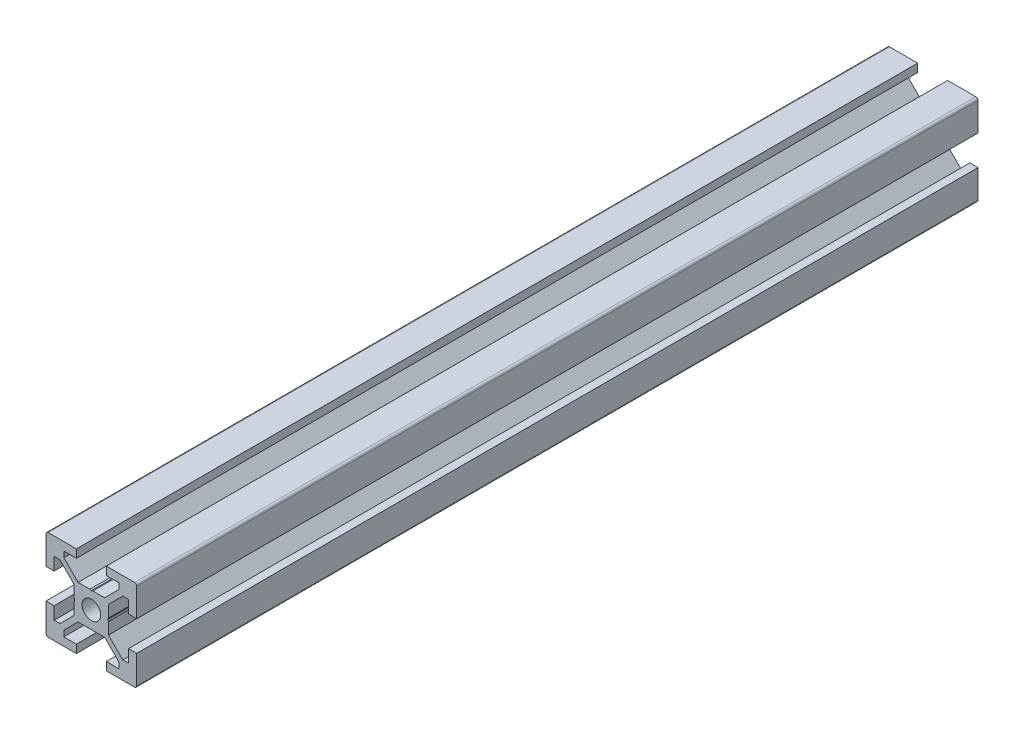
SolidWorks part; units mm, degrees
ref_plane "Front Plane" through (0, 0, 0) normal (0, 0, 1) x (1, 0, 0)
ref_plane "Top Plane" through (0, 0, 0) normal (0, 1, 0) x (1, 0, 0)
ref_plane "Right Plane" through (0, 0, 0) normal (1, 0, 0) x (0, 0, -1)
sketch "Sketch1" plane through (0, 0, 0) normal (0, 0, 1) x (1, 0, 0)
  line L0 (-3.3, 10) -> (-3.3, 8.2)
  line L1 (0, 0) -> (50000, 0) construction
  line L2 (-10, 3.3) -> (-10, 10)
  line L3 (-10, 10) -> (-3.3, 10)
  line L4 (0, 0) -> (0, 50000) construction
  line L5 (-10, -10) -> (10, 10) construction
  line L6 (-10, 10) -> (10, -10) construction
  line L7 (-2.9315, -3.78) -> (-0.34, -3.78)
  line L8 (-3.78, -2.9315) -> (-3.78, -0.34)
  line L9 (-2.9315, 3.78) -> (-0.34, 3.78)
  line L10 (3.78, -2.9315) -> (3.78, -0.34)
  line L11 (-3.78, -3.78) -> (3.78, 3.78) construction
  line L12 (-3.78, 3.78) -> (3.78, -3.78) construction
  line L13 (-6.08, 8.2) -> (-3.3, 8.2)
  line L14 (-8.2, 6.08) -> (-8.2, 3.3)
  line L15 (-8.2, 3.3) -> (-10, 3.3)
  line L16 (-8.2, 6.08) -> (-6.9285, 6.08)
  line L17 (-6.08, 8.2) -> (-6.08, 6.9285)
  line L18 (-6.9285, 6.08) -> (-3.78, 2.9315)
  line L19 (-6.08, 6.9285) -> (-2.9315, 3.78)
  line L20 (8.2, 6.08) -> (6.9285, 6.08)
  line L21 (8.2, 6.08) -> (8.2, 3.3)
  line L22 (8.2, 3.3) -> (10, 3.3)
  line L23 (10, 3.3) -> (10, 10)
  line L24 (10, 10) -> (3.3, 10)
  line L25 (3.3, 10) -> (3.3, 8.2)
  line L26 (6.08, 8.2) -> (3.3, 8.2)
  line L27 (6.08, 8.2) -> (6.08, 6.9285)
  line L28 (6.08, 6.9285) -> (2.9315, 3.78)
  line L29 (6.9285, 6.08) -> (3.78, 2.9315)
  line L30 (6.9285, -6.08) -> (3.78, -2.9315)
  line L31 (6.08, -6.9285) -> (2.9315, -3.78)
  line L32 (6.08, -8.2) -> (6.08, -6.9285)
  line L33 (6.08, -8.2) -> (3.3, -8.2)
  line L34 (3.3, -10) -> (3.3, -8.2)
  line L35 (10, -10) -> (3.3, -10)
  line L36 (10, -3.3) -> (10, -10)
  line L37 (8.2, -3.3) -> (10, -3.3)
  line L38 (8.2, -6.08) -> (8.2, -3.3)
  line L39 (8.2, -6.08) -> (6.9285, -6.08)
  line L40 (-6.08, -6.9285) -> (-2.9315, -3.78)
  line L41 (-6.9285, -6.08) -> (-3.78, -2.9315)
  line L42 (-6.08, -8.2) -> (-6.08, -6.9285)
  line L43 (-8.2, -6.08) -> (-6.9285, -6.08)
  line L44 (-8.2, -3.3) -> (-10, -3.3)
  line L45 (-8.2, -6.08) -> (-8.2, -3.3)
  line L46 (-6.08, -8.2) -> (-3.3, -8.2)
  line L47 (-10, -10) -> (-3.3, -10)
  line L48 (-10, -3.3) -> (-10, -10)
  line L49 (-3.3, -10) -> (-3.3, -8.2)
  line L50 (-0.34, 3.78) -> (0, 3.66)
  line L51 (0.34, 3.78) -> (0, 3.66)
  line L52 (0.34, 3.78) -> (2.9315, 3.78)
  line L53 (-3.78, -0.34) -> (-3.66, 0)
  line L54 (-3.78, 0.34) -> (-3.66, 0)
  line L55 (3.78, 0.34) -> (3.66, 0)
  line L56 (3.78, -0.34) -> (3.66, 0)
  line L57 (-0.34, -3.78) -> (0, -3.66)
  line L58 (0.34, -3.78) -> (0, -3.66)
  line L59 (3.78, 0.34) -> (3.78, 2.9315)
  line L60 (0.34, -3.78) -> (2.9315, -3.78)
  line L61 (-3.78, 0.34) -> (-3.78, 2.9315)
  circle A0 centre (0, 0) radius 2.05
  point P0 (0, 0)
  dimension "D3" = 4.1
  dimension "D1" = 20
  dimension "D2" = 20
  dimension "D4" = 7.56
  dimension "D5" = 6.7
  dimension "D6" = 6.7
  dimension "D7" = 0.6
  dimension "D8" = 3.92
  dimension "D9" = 0.34
  dimension "D10" = 0.12
extrude "Boss-Extrude1" add sketch "Sketch1" along normal blind 185.5
fillet "Fillet1" radius 0.5 4 edges at (-10, 10, 92.75) (-10, -10, 92.75) (10, -10, 92.75) (10, 10, 92.75)
